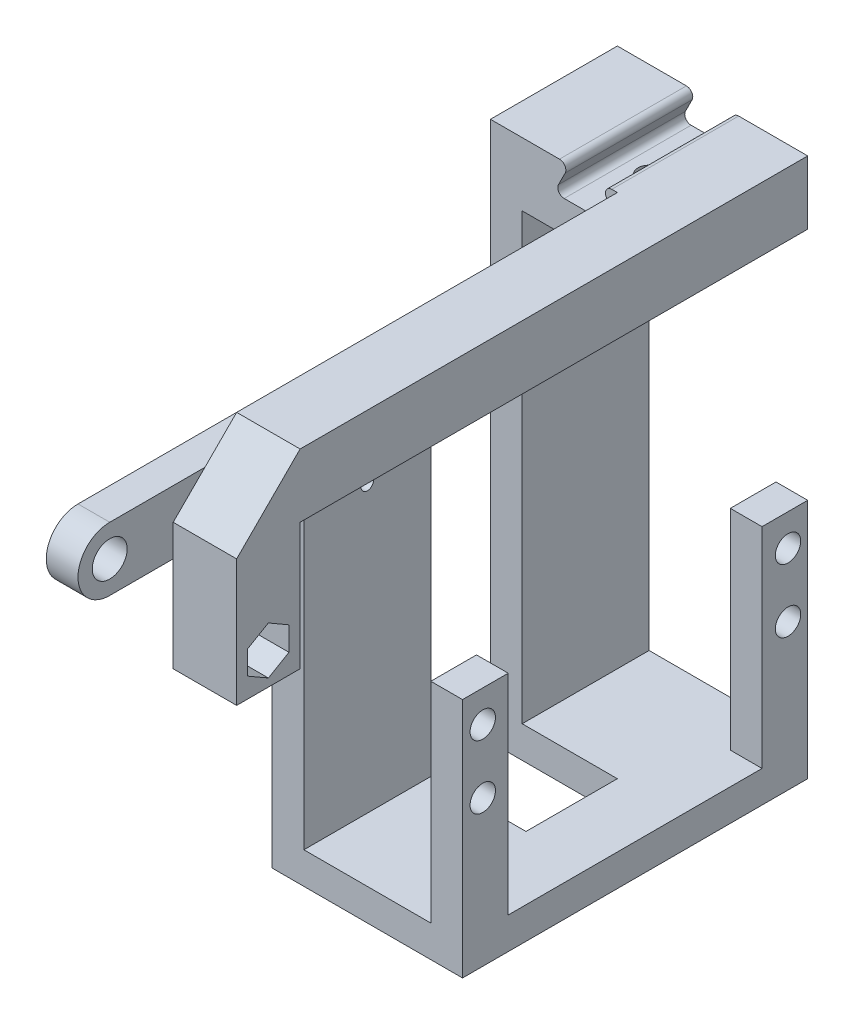
SolidWorks part; units mm, degrees
ref_plane "Plano frontal" through (0, 0, 0) normal (0, 0, 1) x (1, 0, 0)
ref_plane "Plano superior" through (0, 0, 0) normal (0, 1, 0) x (1, 0, 0)
ref_plane "Plano direito" through (0, 0, 0) normal (1, 0, 0) x (0, 0, -1)
sketch "Esboço1" plane through (0, 0, 0) normal (0, 0, 1) x (1, 0, 0)
  line L1 (-15, 45) -> (15, 45)
  line L2 (-15, 45) -> (-15, -45)
  line L3 (-15, -45) -> (15, -45)
  line L4 (15, 45) -> (15, 35)
  line L6 (-15, 35) -> (15, 35)
  line L7 (-10, 35) -> (-10, -45)
  line L8 (-10, -35) -> (15, -35)
  line L9 (10, -35) -> (10, -2)
  line L10 (10, -2) -> (15, -2)
  line L11 (15, -2) -> (15, -35)
  line L12 (15, -35) -> (15, -45)
  line L13 (-2.5, 45) -> (-5, 40)
  line L14 (-5, 40) -> (5, 40)
  line L15 (5, 40) -> (2.5, 45)
  point P1 (-15, 0)
  point P6 (0, 45)
  point P22 (0, 40)
  dimension "D1" = 30
  dimension "D2" = 90
  dimension "D4" = 10
  dimension "D5" = 5
  dimension "D6" = 10
  dimension "D7" = 5
  dimension "D8" = 33
  dimension "D9" = 20
  dimension "D10" = 5
  dimension "D11" = 10
  dimension "D12" = 5
extrude "Ressalto-extrusão1" add sketch "Esboço1" along normal blind 80 contours L15 L14 L13 L1 L2 L6 L4 | L7 L6 L2 L3 | L12 L8 L7 L3 | L11 L10 L9 L8
sketch "Esboço2" plane through (15, 0, 0) normal (1, 0, 0) x (0, 0, -1)
  line L5 (-80, -2) -> (0, -2) construction
  line L6 (-47.2, -2) -> (-7.2, -2)
  line L7 (-47.2, -2) -> (-47.2, -35)
  line L8 (-47.2, -35) -> (-7.2, -35)
  line L9 (-7.2, -2) -> (-7.2, -35)
  line L10 (-80, -45) -> (0, -45) construction
  line L11 (0, -2) -> (0, -45) construction
  line L13 (-80, -2) -> (-54.4, -2)
  line L14 (-80, -2) -> (-80, -35)
  line L15 (-80, -35) -> (-54.4, -35)
  line L16 (-54.4, -2) -> (-54.4, -35)
  dimension "D1" = 10
  dimension "D2" = 40
  dimension "D3" = 7.2
  dimension "D4" = 7.2
extrude "Corte-extrusão1" cut sketch "Esboço2" against normal blind 19
sketch "Esboço4" plane through (10, 0, 0) normal (-1, 0, 0) x (0, 0, 1)
  circle A0 centre (3.1042, -7.0008) radius 2
  circle A1 centre (3.1042, -17.0025) radius 2
  circle A2 centre (51.2105, -17.0025) radius 2
  circle A3 centre (51.2105, -7.0008) radius 2
extrude "Corte-extrusão3" cut sketch "Esboço4" against normal blind 12
sketch "Esboço5" plane through (15, 0, 0) normal (1, 0, 0) x (0, 0, -1)
  line L0 (-90, 35) -> (-80, 45)
  line L1 (-90, 35) -> (-80, 35)
  line L2 (-90, 35) -> (-90, 15)
  line L3 (-90, 15) -> (-80, 15)
  line L4 (-80, 35) -> (-80, 15)
  line L5 (-80, 45) -> (-80, 35)
  line M5 (-80, 45) -> (-80, 35)
  dimension "D1" = 10
  dimension "D2" = 20
extrude "Ressalto-extrusão2" add sketch "Esboço5" against normal blind 10 contours L4 L1 L2 L3 | L0 L1 M5
sketch "Esboço6" plane through (15, 0, 0) normal (1, 0, 0) x (0, 0, -1)
  line L2 (-80, 35) -> (-80, 15) construction
  line L3 (-90, 15) -> (-80, 15) construction
  circle A0 centre (-85, 20) radius 1.75
  dimension "D3" = 3.5
  dimension "D1" = 5
  dimension "D2" = 5
extrude "Corte-extrusão4" cut sketch "Esboço6" against normal blind 15
sketch "Esboço7" plane through (15, 0, 0) normal (1, 0, 0) x (0, 0, -1)
  line L1 (-81.75, 21.8764) -> (-85, 23.7528)
  line L2 (-85, 23.7528) -> (-88.25, 21.8764)
  line L3 (-88.25, 21.8764) -> (-88.25, 18.1236)
  line L4 (-88.25, 18.1236) -> (-85, 16.2472)
  line L5 (-85, 16.2472) -> (-81.75, 18.1236)
  line L6 (-81.75, 18.1236) -> (-81.75, 21.8764)
  circle A0 centre (-85, 20) radius 3.25 construction
  dimension "D1" = 6.5
extrude "Corte-extrusão5" cut sketch "Esboço7" against normal blind 5
sketch "Esboço8" plane through (-15, 0, 0) normal (-1, 0, 0) x (0, 0, 1)
  line L0 (85, 15) -> (80, 15)
  line L1 (80, 15) -> (80, 25)
  line L2 (80, 35) -> (80, 15) construction
  line L3 (80, 25) -> (85, 25)
  circle A0 centre (85, 20) radius 2.75
  circle A1 centre (85, 20) radius 5
  line M3 (80, -45) -> (80, 45)
  dimension "D1" = 5.5
extrude "Ressalto-extrusão3" add sketch "Esboço8" against normal blind 5 contours A1 L3 L1 | A1 A0 | A1 L0 M3
sketch "Esboço9" plane through (0, 0, 80) normal (0, 0, 1) x (1, 0, 0)
  line L0 (-10, 15) -> (-10, -35) construction
  line L1 (-15, -45) -> (-10, -45)
  line L2 (-15, -45) -> (-15, 15)
  line L3 (-15, 15) -> (-10, 15)
  line L4 (-10, -45) -> (-10, 15)
  line L6 (-10, -45) -> (15, -45)
  line L7 (-10, -45) -> (-10, -35)
  line L8 (-10, -35) -> (15, -35)
  line L9 (15, -45) -> (15, -35)
  line L10 (-10, 15) -> (-15, 15) construction
  line L12 (-15, 25) -> (5, 25)
  line L13 (-15, 25) -> (-15, 45)
  line L14 (-15, 45) -> (5, 45)
  line L15 (5, 25) -> (5, 45)
  line M2 (-10, -35) -> (-10, 15)
  line M3 (-10, 15) -> (-15, 15)
  line M4 (-15, 15) -> (-15, -45)
  line M5 (-15, -45) -> (15, -45)
  line M6 (15, -45) -> (15, -35)
  line M7 (15, -35) -> (-10, -35)
extrude "Corte-extrusão6" cut sketch "Esboço9" against normal up to surface (25.6 mm away) contours L12 L15 L14 L13 | L4 M5 M2 M3 M4 | L4 M5 M6 M7 up to face at (12.5, -18.5, 54.4)
sketch "Esboço11" plane through (-15, 0, 0) normal (-1, 0, 0) x (0, 0, 1)
  line L0 (54.4, -45) -> (0, -45) construction
  line L1 (54.4, 45) -> (20, 45)
  line L2 (54.4, 45) -> (54.4, 25)
  line L3 (54.4, 25) -> (20, 25)
  line L4 (20, 45) -> (20, 25)
  line L5 (34.4, -45) -> (20, -45)
  line L6 (34.4, -45) -> (34.4, 15)
  line L7 (34.4, 15) -> (20, 15)
  line L8 (20, -45) -> (20, 15)
  line L9 (0, 45) -> (0, -45) construction
  line L10 (54.4, 15) -> (54.4, -45) construction
  line L11 (54.4, 25) -> (85, 25) construction
  line L13 (85, 15) -> (54.4, 15) construction
  dimension "D1" = 20
  dimension "D2" = 20
  dimension "D3" = 20
extrude "Corte-extrusão7" cut sketch "Esboço11" against normal up to surface (20 mm away)
sketch "Esboço12" plane through (0, 40, 0) normal (0, 1, 0) x (1, 0, 0)
  line L0 (15, -80) -> (15, 0) construction
  line L1 (5, -20) -> (-5, -20) construction
  circle A0 centre (0, -10) radius 1.75
  dimension "D1" = 3.5
  dimension "D2" = 15
  dimension "D3" = 10
extrude "Corte-extrusão8" cut sketch "Esboço12" against normal blind 25
sketch "Esboço13" plane through (0, 35, 0) normal (0, -1, 0) x (1, 0, 0)
  line L1 (0, 6.2472) -> (3.25, 8.1236)
  line L2 (3.25, 8.1236) -> (3.25, 11.8764)
  line L3 (3.25, 11.8764) -> (0, 13.7528)
  line L4 (0, 13.7528) -> (-3.25, 11.8764)
  line L5 (-3.25, 11.8764) -> (-3.25, 8.1236)
  line L6 (-3.25, 8.1236) -> (0, 6.2472)
  circle A0 centre (0, 10) radius 3.25 construction
  dimension "D1" = 6.5
extrude "Corte-extrusão9" cut sketch "Esboço13" against normal blind 2.5
fillet "Filete1" radius 1 2 edges at (-2.5, 45, 10) (2.5, 45, 10)
fillet "Filete2" radius 1 2 edges at (-5, 40, 10) (5, 40, 10)
sketch "Esboço15" plane through (0, 0, 54.4) normal (0, 0, 1) x (1, 0, 0)
  line L0 (15, -45) -> (15, -2) construction
  line L1 (-15, -45) -> (15, -45)
  line L2 (-15, -45) -> (-15, -40)
  line L3 (-15, -40) -> (15, -40)
  line L4 (15, -45) -> (15, -40)
  dimension "D1" = 5
extrude "Corte-extrusão11" cut sketch "Esboço15" against normal blind 120
sketch "Esboço16" plane through (-10, 0, 0) normal (1, 0, 0) x (0, 0, -1)
  line L0 (-20, 25) -> (-85, 25) construction
  line L1 (-34.4, 15) -> (-34.4, -35) construction
  line L2 (-20, 15) -> (-34.4, 15) construction
  circle A0 centre (-29.4, 20) radius 1
  circle A1 centre (-44.4, 10) radius 1
  dimension "D3" = 2
  dimension "D4" = 2
  dimension "D1" = 5
  dimension "D2" = 5
  dimension "D5" = 10
  dimension "D6" = 5
extrude "Corte-extrusão12" cut sketch "Esboço16" against normal blind 2
